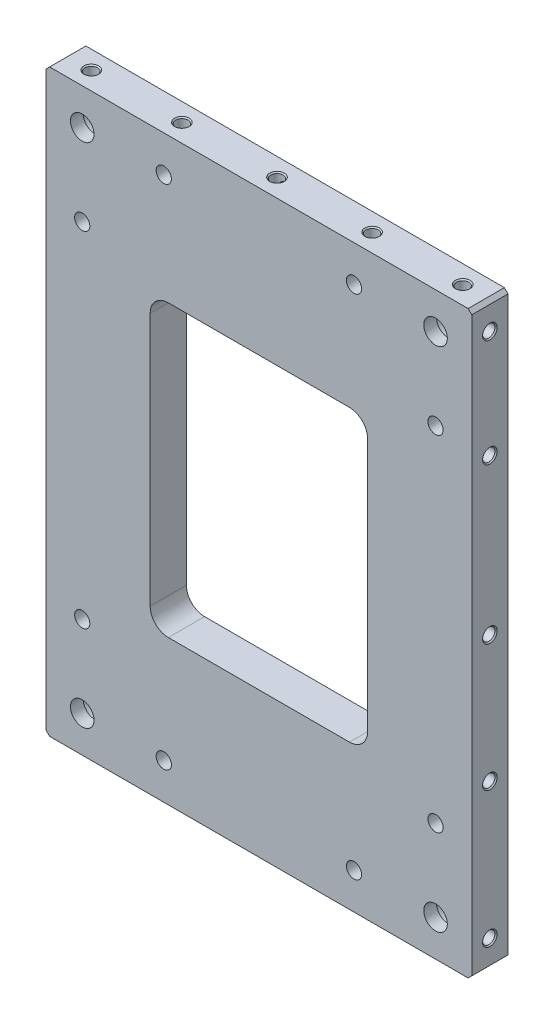
SolidWorks part; units mm, degrees
material "6061 Alloy"
ref_plane "Front Plane" through (0, 0, 0) normal (0, 0, 1) x (1, 0, 0)
ref_plane "Top Plane" through (0, 0, 0) normal (0, 1, 0) x (1, 0, 0)
ref_plane "Right Plane" through (0, 0, 0) normal (1, 0, 0) x (0, 0, -1)
sketch "Sketch1" plane through (0, 0, 0) normal (0, 0, 1) x (1, 0, 0)
  line L1 (-117.5, 160) -> (117.5, 160)
  line L2 (-117.5, 160) -> (-117.5, -160)
  line L3 (-117.5, -160) -> (117.5, -160)
  line L4 (117.5, 160) -> (117.5, -160)
  line L5 (-117.5, 160) -> (117.5, -160) construction
  line L6 (-117.5, -160) -> (117.5, 160) construction
  dimension "D1" = 320
  dimension "D2" = 235
extrude "Boss-Extrude1" add sketch "Sketch1" along normal blind 20
sketch "Sketch2" plane through (0, 0, 20) normal (0, 0, 1) x (1, 0, 0)
  line L1 (-60, 80) -> (60, 80)
  line L2 (-60, 80) -> (-60, -80)
  line L3 (-60, -80) -> (60, -80)
  line L4 (60, 80) -> (60, -80)
  line L5 (-60, 80) -> (60, -80) construction
  line L6 (-60, -80) -> (60, 80) construction
  point P0 (0, 0)
  dimension "D1" = 120
  dimension "D2" = 160
extrude "Cut-Extrude1" cut sketch "Sketch2" against normal through all
fillet "Fillet1" radius 10 4 edges at (-60, -80, 10) (60, 80, 10) (60, -80, 10) (-60, 80, 10)
sketch "Sketch3" plane through (0, 0, 0) normal (0, 0, -1) x (-1, 0, 0)
  line L0 (-60, 0) -> (60, 0) construction
  line L3 (0, 11) -> (0, -11) construction
  line L4 (0, 80) -> (0, -80) construction
  line L5 (-50, 80) -> (50, 80) construction
  line L6 (50, -80) -> (-50, -80) construction
  line L7 (60, 70) -> (60, -70) construction
  line L8 (-60, -70) -> (-60, 70) construction
  point P0 (-95, 65)
  point P1 (-105, 0)
  point P2 (-95, -65)
  point P3 (0, 155)
  point P11 (-65, 145)
  point P15 (65, 145)
  dimension "D2" = 95
  dimension "D3" = 65
  dimension "D4" = 65
  dimension "D5" = 155
  dimension "D6" = 10
  dimension "D7" = 10
hole_wizard "M3 Tapped Hole1" positions "Sketch4" profile "Sketch6" tap size "M3" standard "GB"
sketch "Sketch4" plane through (0, 0, 0) normal (0, 0, -1) x (-1, 0, 0)
  point P0 (-95, 65)
  point P2 (-105, 0)
  point P4 (-95, -65)
  point P6 (-65, 145)
  point P8 (0, 155)
  point P10 (65, 145)
sketch "Sketch6" plane through (95, 65, 0) normal (1, 0, 0) x (0, 1, 0)
  line L0 (0, 0) -> (0, 10.7511)
  line L1 (0, 10.7511) -> (1.25, 10)
  line L2 (1.25, 10) -> (1.25, 0.275)
  line L3 (1.25, 0.275) -> (1.525, 0)
  line L5 (1.525, 0) -> (0, 0)
  line L6 (-1.25, 0.275) -> (-1.525, 0) construction
  line L10 (0, 10.7511) -> (-1.25, 10) construction
  line L11 (0, -6.35) -> (0, 107.95) construction
  dimension "Tap Drill Dia." = 2.5
  dimension "Tap Drill Depth" = 10
  dimension "Near C'Sink Dia." = 3.05
  dimension "Near C'Sink Angle" = 90
  dimension "Drill Angle" = 118
sketch "Sketch7" plane through (0, 0, 0) normal (0, 0, -1) x (-1, 0, 0)
  point P0 (110, -105)
  point P1 (80, -140)
  point P2 (65, -140)
  point P9 (110, -120)
  point P10 (110, -140)
  dimension "D1" = 140
  dimension "D2" = 15
  dimension "D3" = 30
  dimension "D4" = 20
  dimension "D5" = 15
  dimension "D6" = 110
hole_wizard "M3 Tapped Hole2" positions "Sketch10" profile "Sketch12" tap size "M3" standard "GB"
sketch "Sketch10" plane through (0, 0, 0) normal (0, 0, -1) x (-1, 0, 0)
  point P0 (110, -105)
  point P2 (80, -140)
  point P4 (65, -140)
  point P12 (110, -120)
sketch "Sketch12" plane through (-110, -105, 0) normal (1, 0, 0) x (0, 1, 0)
  line L0 (0, 0) -> (0, 8.7511)
  line L1 (0, 8.7511) -> (1.25, 8)
  line L2 (1.25, 8) -> (1.25, 0.275)
  line L3 (1.25, 0.275) -> (1.525, 0)
  line L5 (1.525, 0) -> (0, 0)
  line L6 (-1.25, 0.275) -> (-1.525, 0) construction
  line L10 (0, 8.7511) -> (-1.25, 8) construction
  line L11 (0, -6.35) -> (0, 107.95) construction
  dimension "Tap Drill Dia." = 2.5
  dimension "Tap Drill Depth" = 8
  dimension "Near C'Sink Dia." = 3.05
  dimension "Near C'Sink Angle" = 90
  dimension "Drill Angle" = 118
sketch "Sketch13" plane through (0, 0, 0) normal (0, 0, -1) x (-1, 0, 0)
  line L0 (-117.5, 160) -> (117.5, 160) construction
  line L1 (-117.5, -160) -> (-117.5, 160) construction
  line L2 (117.5, 160) -> (117.5, -160) construction
  line L3 (11, 0) -> (-11, 0) construction
  line L4 (0, 11) -> (0, -11) construction
  point P0 (-97.5, 140)
  point P1 (-52.5, 140)
  point P4 (-97.5, 95)
  point P9 (97.5, 140)
  point P12 (52.5, 140)
  point P13 (52.5, -140)
  point P14 (97.5, -140)
  point P15 (-52.5, -140)
  point P16 (-97.5, -140)
  point P22 (97.5, 95)
  point P23 (97.5, -95)
  point P24 (-97.5, -95)
  dimension "D1" = 20
  dimension "D2" = 20
  dimension "D3" = 20
  dimension "D4" = 20
  dimension "D5" = 45
  dimension "D6" = 45
  dimension "D7" = 45
hole_wizard "CBORE for M8 Hexagon socket head cap screws1" positions "Sketch14" profile "Sketch15" counterbore size "M8" standard "GB" end condition through all
sketch "Sketch14" plane through (0, 0, 0) normal (0, 0, -1) x (-1, 0, 0)
  point P3 (-52.5, 140)
  point P6 (-97.5, 95)
  point P9 (52.5, 140)
  point P15 (97.5, 95)
  point P18 (-97.5, -95)
  point P24 (-52.5, -140)
  point P27 (52.5, -140)
  point P33 (97.5, -95)
sketch "Sketch15" plane through (52.5, 140, 0) normal (1, 0, 0) x (0, 1, 0)
  line L0 (0, 0) -> (0, 20)
  line L1 (0, 20) -> (4.2, 20)
  line L3 (4.2, 20) -> (4.2, 9)
  line L4 (4.2, 9) -> (7.5, 9)
  line L5 (7.5, 9) -> (7.5, 0)
  line L7 (7.5, 0) -> (0, 0)
  line L11 (0, -6.35) -> (0, 107.95) construction
  dimension "Thru Hole Dia." = 8.4
  dimension "Thru Hole Depth" = 20
  dimension "C'Bore Dia." = 15
  dimension "C'Bore Depth" = 9
hole_wizard "CBORE for M12 Hexagon socket head cap screws2" positions "Sketch20" profile "Sketch21" counterbore size "M12" standard "GB" end condition through all
sketch "Sketch20" plane through (0, 0, 0) normal (0, 0, -1) x (-1, 0, 0)
  point P0 (-97.5, 140)
  point P3 (97.5, 140)
  point P6 (-97.5, -140)
  point P9 (97.5, -140)
sketch "Sketch21" plane through (97.5, 140, 0) normal (1, 0, 0) x (0, 1, 0)
  line L0 (0, 0) -> (0, 20)
  line L1 (0, 20) -> (6.5, 20)
  line L3 (6.5, 20) -> (6.5, 13)
  line L4 (6.5, 13) -> (10, 13)
  line L5 (10, 13) -> (10, 0)
  line L7 (10, 0) -> (0, 0)
  line L11 (0, -6.35) -> (0, 107.95) construction
  dimension "Thru Hole Dia." = 13
  dimension "Thru Hole Depth" = 20
  dimension "C'Bore Dia." = 20
  dimension "C'Bore Depth" = 13
sketch "Sketch22" plane through (0, 160, 0) normal (0, 1, 0) x (1, 0, 0)
  line L0 (0, -11) -> (0, 11) construction
  line L1 (-117.5, -10) -> (117.5, -10) construction
  line L2 (-117.5, -20) -> (-117.5, 0) construction
  line L5 (117.5, -20) -> (117.5, 0) construction
  point P0 (-102.5, -10)
  point P3 (102.5, -10)
  point P9 (52.5, -10)
  point P10 (-52.5, -10)
  point P13 (0, -10)
  dimension "D1" = 15
  dimension "D3" = 50
hole_wizard "M8 Tapped Hole1" positions "Sketch23" profile "Sketch24" tap size "M8" standard "GB"
sketch "Sketch23" plane through (0, 160, 0) normal (0, 1, 0) x (1, 0, 0)
  point P0 (-102.5, -10)
  point P2 (0, -10)
  point P4 (102.5, -10)
  point P19 (-52.5, -10)
  point P28 (52.5, -10)
sketch "Sketch24" plane through (-102.5, 160, 10) normal (1, 0, 0) x (0, 0, 1)
  line L0 (0, 0) -> (0, 10.5429)
  line L1 (0, 10.5429) -> (3.4, 8.5)
  line L2 (3.4, 8.5) -> (3.4, 0.625)
  line L3 (3.4, 0.625) -> (4.025, 0)
  line L5 (4.025, 0) -> (0, 0)
  line L6 (-3.4, 0.625) -> (-4.025, 0) construction
  line L10 (0, 10.5429) -> (-3.4, 8.5) construction
  line L11 (0, -6.35) -> (0, 107.95) construction
  dimension "Tap Drill Dia." = 6.8
  dimension "Tap Drill Depth" = 8.5
  dimension "Near C'Sink Dia." = 8.05
  dimension "Near C'Sink Angle" = 90
  dimension "Drill Angle" = 118
mirror "Mirror1" about plane through (0, 0, 0) normal (0, 1, 0) of "M8 Tapped Hole1"
chamfer "Chamfer1" distance 2 angle 45 4 edges at (117.5, -160, 10) (117.5, 160, 10) (-117.5, -160, 10) (-117.5, 160, 10)
sketch "Sketch25" plane through (-117.5, 0, 0) normal (-1, 0, 0) x (0, 0, 1)
  line L0 (10, 160) -> (10, -160) construction
  line L1 (20, -160) -> (0, -160) construction
  line L2 (11, 0) -> (-11, 0) construction
  point P5 (10, -145)
  point P6 (10, -70)
  point P7 (10, 0)
  point P10 (10, 70)
  point P11 (10, 145)
  dimension "D1" = 15
  dimension "D2" = 75
hole_wizard "M8 Tapped Hole2" positions "Sketch26" profile "Sketch27" tap size "M8" standard "GB"
sketch "Sketch26" plane through (-117.5, 0, 0) normal (-1, 0, 0) x (0, 0, 1)
  line L0 (10, 160) -> (10, -160) construction
  point P0 (10, 145)
  point P3 (10, 85.7105)
  point P7 (10, 0)
  point P9 (10, -70)
  point P12 (10, -145)
sketch "Sketch27" plane through (-117.5, 145, 10) normal (0, 1, 0) x (0, 0, 1)
  line L0 (0, 0) -> (0, 10.0429)
  line L1 (0, 10.0429) -> (3.4, 8)
  line L2 (3.4, 8) -> (3.4, 0.625)
  line L3 (3.4, 0.625) -> (4.025, 0)
  line L5 (4.025, 0) -> (0, 0)
  line L6 (-3.4, 0.625) -> (-4.025, 0) construction
  line L10 (0, 10.0429) -> (-3.4, 8) construction
  line L11 (0, -6.35) -> (0, 107.95) construction
  dimension "Tap Drill Dia." = 6.8
  dimension "Tap Drill Depth" = 8
  dimension "Near C'Sink Dia." = 8.05
  dimension "Near C'Sink Angle" = 90
  dimension "Drill Angle" = 118
mirror "Mirror2" about plane through (0, 0, 0) normal (1, 0, 0) of "M8 Tapped Hole2"
